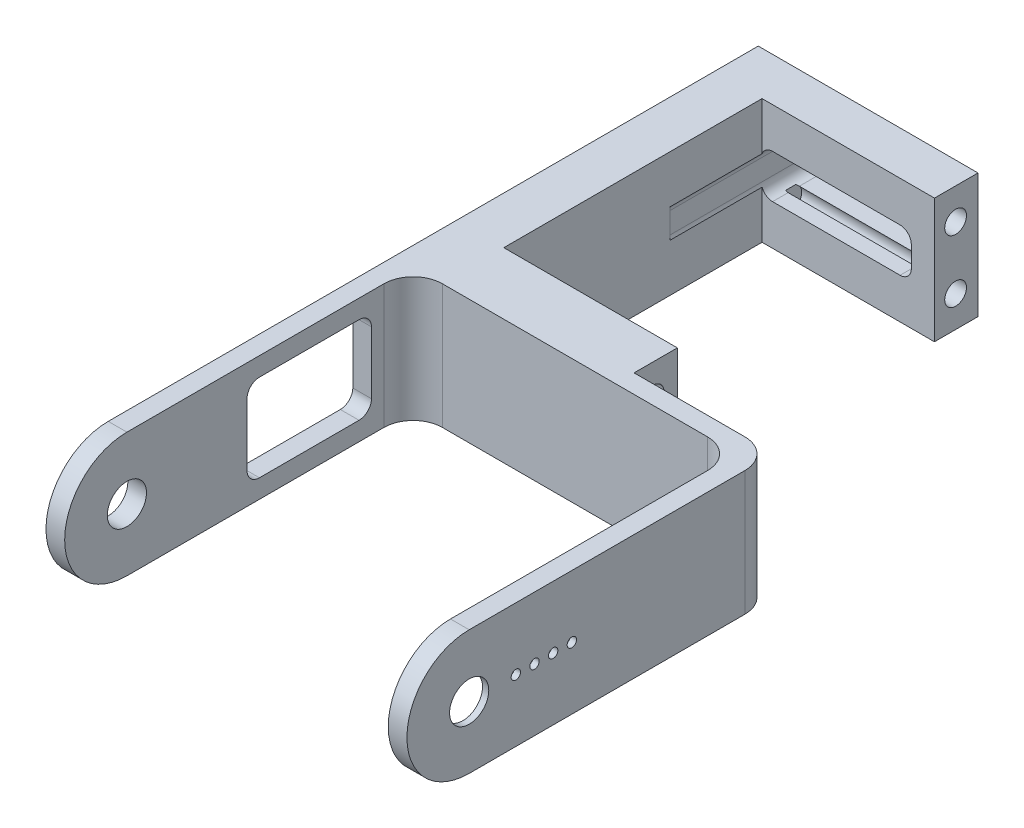
SolidWorks part; units mm, degrees
ref_plane "Vorne" through (0, 0, 0) normal (0, 0, 1) x (1, 0, 0)
ref_plane "Oben" through (0, 0, 0) normal (0, 1, 0) x (1, 0, 0)
ref_plane "Rechts" through (0, 0, 0) normal (1, 0, 0) x (0, 0, -1)
sketch "Skizze1" plane through (0, 0, 0) normal (0, 1, 0) x (1, 0, 0)
  line L1 (0, 0) -> (58, 0)
  line L2 (0, 0) -> (0, 59)
  line L3 (0, 59) -> (53.3, 59)
  line L4 (58, 0) -> (58, 54.3)
  line L5 (55, 0) -> (3, 0)
  line L6 (55, 0) -> (55, 51.3)
  line L7 (50.3, 56) -> (7.7, 56)
  line L8 (3, 0) -> (3, 51.3)
  arc A0 (55, 51.3) -> (50.3, 56) centre (50.3, 51.3) ccw
  arc A1 (7.7, 56) -> (3, 51.3) centre (7.7, 51.3) ccw
  arc A2 (53.3, 59) -> (58, 54.3) centre (53.3, 54.3) cw
  dimension "D6" = 4.7
  dimension "D7" = 4.7
  dimension "D1" = 59
  dimension "D2" = 58
  dimension "D3" = 3
  dimension "D4" = 3
  dimension "D5" = 3
extrude "Aufsatz-Linear austragen1" add sketch "Skizze1" along normal blind 20 contours L1 L8 L7 L6 L4 L3 L2
sketch "Skizze2" plane through (58, 0, 0) normal (1, 0, 0) x (0, 0, -1)
  line L0 (0, 20) -> (0, 0) construction
  line L1 (10, 20) -> (0, 20)
  line L2 (0, 20) -> (0, 0)
  line L3 (0, 0) -> (10, 0)
  arc A0 (10, 20) -> (10, 0) centre (10, 10) ccw
  line M1 (0, 0) -> (54.3, 0)
  line M3 (54.3, 20) -> (0, 20)
  line M4 (0, 20) -> (0, 0)
  dimension "D1" = 10
extrude "Schnitt-Linear austragen1" cut sketch "Skizze2" against normal through all contours A0 M3 M4 | A0 L2 M1
sketch "Skizze3" plane through (58, 0, 0) normal (1, 0, 0) x (0, 0, -1)
  circle A0 centre (10, 10) radius 3.15
  dimension "D1" = 6.3
extrude "Schnitt-Linear austragen2" cut sketch "Skizze3" against normal through all
sketch "Skizze4" plane through (55, 0, 0) normal (-1, 0, 0) x (0, 0, 1)
  line L2 (-27.5, 7.5) -> (-12.8239, 4.1455)
  line L3 (-27.5, 12.5) -> (-12.8239, 15.8545)
  arc A0 (-12.8239, 4.1455) -> (-12.8239, 15.8545) centre (-10, 10) ccw
  arc A1 (-27.5, 12.5) -> (-27.5, 7.5) centre (-27.5, 10) ccw
  arc A2 (-10, 0) -> (-10, 20) centre (-10, 10) ccw construction
  dimension "D1" = 0
extrude "Schnitt-Linear austragen3" cut sketch "Skizze4" against normal blind 2
sketch "Skizze5" plane through (57, 0, 0) normal (-1, 0, 0) x (0, 0, 1)
  circle A0 centre (-26.5, 10) radius 0.75
  circle A1 centre (-23.5, 10) radius 0.75
  circle A2 centre (-20.5, 10) radius 0.75
  circle A3 centre (-17.5, 10) radius 0.75
  circle A4 centre (-10, 10) radius 3.15 construction
  dimension "D1" = 3
  dimension "D2" = 3
  dimension "D3" = 3
  dimension "D4" = 7.5
  dimension "D5" = 0
extrude "Schnitt-Linear austragen4" cut sketch "Skizze5" against normal blind 2
sketch "Skizze6" plane through (0, 0, 0) normal (0, -1, 0) x (1, 0, 0)
  line L0 (0, -59) -> (53.3, -59) construction
  line L3 (35.5, -65.9553) -> (0, -65.9553)
  line L4 (0, -59) -> (0, -65.9553)
  line L7 (0, -59) -> (35.5, -59)
  line L9 (35.5, -65.9553) -> (35.5, -59)
  line L10 (0, -10) -> (0, -59) construction
  dimension "D1" = 0
  dimension "D2" = 6.9553
  dimension "D3" = 35.5
  dimension "D4" = 35.5
extrude "Aufsatz-Linear austragen2" add sketch "Skizze6" against normal blind 20
sketch "Skizze7" plane through (0, 0, 0) normal (0, -1, 0) x (1, 0, 0)
  line L0 (0, -65.9553) -> (35.5, -65.9553) construction
  line L1 (0, -65.9553) -> (7.6117, -65.9553)
  line L2 (0, -65.9553) -> (0, -119.1478)
  line L3 (0, -119.1478) -> (7.6117, -119.1478)
  line L4 (7.6117, -65.9553) -> (7.6117, -119.1478)
  dimension "D1" = 7.6117
  dimension "D2" = 53.1925
extrude "Aufsatz-Linear austragen3" add sketch "Skizze7" against normal blind 20
sketch "Skizze8" plane through (7.6117, 0, 0) normal (1, 0, 0) x (0, 0, -1)
  line L0 (65.9553, 20) -> (65.9553, 0) construction
  line L1 (114.4553, 20) -> (107.4553, 20)
  line L2 (114.4553, 20) -> (114.4553, 0)
  line L3 (114.4553, 0) -> (107.4553, 0)
  line L4 (107.4553, 20) -> (107.4553, 0)
  line L5 (119.1478, 0) -> (65.9553, 0) construction
  dimension "D1" = 0
  dimension "D2" = 41.5
  dimension "D3" = 7
  dimension "D4" = 20
extrude "Aufsatz-Linear austragen4" add sketch "Skizze8" along normal blind 27.7
sketch "Skizze9" plane through (0, 0, -119.1478) normal (0, 0, -1) x (-1, 0, 0)
  line L0 (0, 20) -> (-7.6117, 20) construction
  line L1 (-9.3, 13.5) -> (-29.794, 13.5)
  line L2 (-7.5, 11.7) -> (-7.5, 8.3)
  line L3 (-9.3, 6.5) -> (-29.794, 6.5)
  line L4 (-31.594, 11.7) -> (-31.594, 8.3)
  line L5 (0, 0) -> (-7.6117, 0) construction
  line L7 (0, 20) -> (0, 0) construction
  arc A0 (-9.3, 13.5) -> (-7.5, 11.7) centre (-9.3, 11.7) cw
  arc A1 (-7.5, 8.3) -> (-9.3, 6.5) centre (-9.3, 8.3) cw
  arc A2 (-29.794, 6.5) -> (-31.594, 8.3) centre (-29.794, 8.3) cw
  arc A3 (-29.794, 13.5) -> (-31.594, 11.7) centre (-29.794, 11.7) ccw
  dimension "D5" = 1.8
  dimension "D1" = 6.5
  dimension "D2" = 6.5
  dimension "D4" = 7.5
extrude "Schnitt-Linear austragen5" cut sketch "Skizze9" against normal blind 26.48
sketch "Skizze10" plane through (35.3117, 0, 0) normal (1, 0, 0) x (0, 0, -1)
  line L1 (59, 20) -> (59, 0) construction
  line L2 (114.4553, 20) -> (107.4553, 20) construction
  line L3 (107.4553, 0) -> (114.4553, 0) construction
  line L4 (65.9553, 0) -> (59, 0) construction
  line L5 (65.9553, 20) -> (59, 20) construction
  circle A4 centre (62.0553, 15) radius 1.75
  circle A5 centre (62.0553, 5) radius 1.75
  circle A6 centre (110.8553, 5) radius 1.75
  circle A7 centre (110.8553, 15) radius 1.75
  dimension "D1" = 3.5
  dimension "D2" = 3.5
  dimension "D3" = 3.5
  dimension "D4" = 3.5
  dimension "D5" = 3.0553
  dimension "D6" = 3.0553
  dimension "D7" = 51.8553
  dimension "D8" = 51.8553
  dimension "D9" = 5
  dimension "D10" = 5
  dimension "D11" = 5
  dimension "D12" = 5
extrude "Schnitt-Linear austragen6" cut sketch "Skizze10" against normal blind 26.48 and the other way blind 6
sketch "Skizze11" plane through (0, 0, 0) normal (-1, 0, 0) x (0, 0, 1)
  line L1 (-107.4553, 7.6757) -> (-107.4553, 0) construction
  line L2 (-10, 0) -> (-119.1478, 0) construction
  circle A1 centre (-96.9553, 10) radius 3
  dimension "D1" = 6
  dimension "D2" = 10.5
  dimension "D3" = 10
extrude "Aufsatz-Linear austragen5" add sketch "Skizze11" along normal blind 4
sketch "Skizze12" plane through (7.6117, 0, 0) normal (1, 0, 0) x (0, 0, -1)
  line L1 (114.4553, 20) -> (119.1478, 20)
  line L2 (114.4553, 20) -> (114.4553, 0)
  line L3 (114.4553, 0) -> (119.1478, 0)
  line L4 (119.1478, 20) -> (119.1478, 0)
extrude "Schnitt-Linear austragen7" cut sketch "Skizze12" against normal through all
sketch "Skizze13" plane through (0, 0, 0) normal (-1, 0, 0) x (0, 0, 1)
  line L0 (-10, 0) -> (-114.4553, 0) construction
  line L1 (-47.3, 3) -> (-31.3, 3)
  line L2 (-49.3, 5) -> (-49.3, 15)
  line L3 (-47.3, 17) -> (-31.3, 17)
  line L4 (-29.3, 5) -> (-29.3, 15)
  line L5 (-10, 20) -> (-114.4553, 20) construction
  line L6 (-51.3, 20) -> (-51.3, 0) construction
  arc A0 (-31.3, 3) -> (-29.3, 5) centre (-31.3, 5) ccw
  arc A1 (-31.3, 17) -> (-29.3, 15) centre (-31.3, 15) cw
  arc A2 (-49.3, 15) -> (-47.3, 17) centre (-47.3, 15) cw
  arc A3 (-47.3, 3) -> (-49.3, 5) centre (-47.3, 5) cw
  point P14 (-29.3, 17)
  point P17 (-49.3, 17)
  dimension "D5" = 2
  dimension "D1" = 3
  dimension "D2" = 3
  dimension "D3" = 2
  dimension "D4" = 20
extrude "Schnitt-Linear austragen8" cut sketch "Skizze13" against normal blind 6.73
